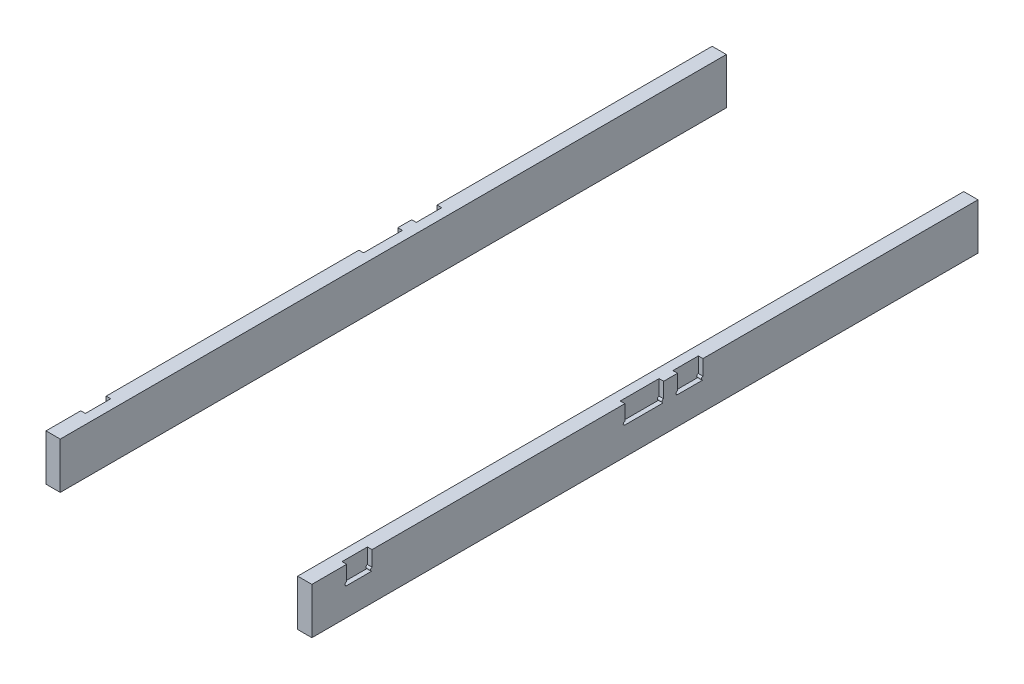
SolidWorks part; units mm, degrees
ref_plane "Front Plane" through (0, 0, 0) normal (0, 0, 1) x (1, 0, 0)
ref_plane "Top Plane" through (0, 0, 0) normal (0, 1, 0) x (1, 0, 0)
ref_plane "Right Plane" through (0, 0, 0) normal (1, 0, 0) x (0, 0, -1)
ref_plane "Plane2" through (-287.55, 0, 0) normal (-1, 0, 0) x (0, 0, 1)
sketch "Sketch8" plane through (-287.55, 0, 0) normal (-1, 0, 0) x (0, 0, 1)
  line L0 (1471.6, -400) -> (30.8, -400)
  line L1 (30.8, -400) -> (30.8, -500)
  line L2 (30.8, -500) -> (1471.6, -500)
  line L3 (1471.6, -500) -> (1471.6, -400)
  dimension "D1" = 100
  dimension "D2" = 1440.8
extrude "Boss-Extrude2" add sketch "Sketch8" against normal blind 30.8 separate body
sketch "Sketch9" plane through (-287.55, 0, 0) normal (-1, 0, 0) x (0, 0, 1)
  line L0 (680.67, -433) -> (680.67, -400)
  line L1 (680.67, -400) -> (625.67, -400)
  line L2 (625.67, -400) -> (625.67, -433)
  line L3 (625.67, -440) -> (680.67, -440)
  line L4 (30.8, -400) -> (30.8, -500) construction
  arc A0 (625.67, -433) -> (625.67, -440) centre (625.67, -436.5) ccw
  arc A1 (680.67, -440) -> (680.67, -433) centre (680.67, -436.5) ccw
  dimension "D6" = 3.5
  dimension "D7" = 3.5
  dimension "D1" = 594.87
  dimension "D2" = 55
  dimension "D3" = 36.5
  dimension "D4" = 36.5
  dimension "D5" = 40
extrude "Cut-Extrude4" cut sketch "Sketch9" against normal blind 10
sketch "Sketch10" plane through (-287.55, 0, 0) normal (-1, 0, 0) x (0, 0, 1)
  line L0 (794.66, -433.0349) -> (794.66, -400)
  line L1 (794.66, -400) -> (710.67, -400)
  line L2 (710.67, -400) -> (710.67, -433.0834)
  line L3 (709.9103, -440) -> (795.1527, -440)
  line L4 (680.67, -433) -> (680.67, -400) construction
  arc A0 (710.67, -433.0834) -> (709.9103, -440) centre (709.9103, -436.5) cw
  arc A1 (795.1527, -440) -> (794.66, -433.0349) centre (795.1527, -436.5) ccw
  dimension "D5" = 3.5
  dimension "D6" = 3.5
  dimension "D1" = 30
  dimension "D2" = 40
  dimension "D3" = 36.5
  dimension "D4" = 36.5
  dimension "D7" = 83.99
extrude "Cut-Extrude5" cut sketch "Sketch10" against normal blind 10
sketch "Sketch11" plane through (-287.55, 0, 0) normal (-1, 0, 0) x (0, 0, 1)
  line L0 (1396.47, -433.0349) -> (1396.47, -400)
  line L1 (1396.47, -400) -> (1341.47, -400)
  line L2 (1341.47, -400) -> (1341.47, -433.0834)
  line L3 (1340.7103, -440) -> (1396.9627, -440)
  line L4 (794.66, -433.0349) -> (794.66, -400) construction
  arc A0 (1341.47, -433.0834) -> (1340.7103, -440) centre (1340.7103, -436.5) cw
  arc A1 (1396.9627, -440) -> (1396.47, -433.0349) centre (1396.9627, -436.5) ccw
  dimension "D5" = 3.5
  dimension "D7" = 3.5
  dimension "D1" = 546.81
  dimension "D2" = 40
  dimension "D3" = 55
  dimension "D4" = 36.5
  dimension "D6" = 36.5
extrude "Cut-Extrude6" cut sketch "Sketch11" against normal blind 10
ref_plane "Plane3" through (287.55, 0, 0) normal (1, 0, 0) x (0, 0, -1)
sketch "Sketch16" plane through (287.55, 0, 0) normal (1, 0, 0) x (0, 0, -1)
  line L0 (-30.8, -400) -> (-1471.6, -400)
  line L1 (-1471.6, -400) -> (-1471.6, -500)
  line L2 (-1471.6, -500) -> (-30.8, -500)
  line L3 (-30.8, -500) -> (-30.8, -400)
  line L4 (-30.8, -400) -> (-30.8, -500) construction
  dimension "D1" = 100
  dimension "D2" = 1440.8
extrude "Boss-Extrude3" add sketch "Sketch16" against normal blind 30.8 separate body
sketch "Sketch17" plane through (287.55, 0, 0) normal (1, 0, 0) x (0, 0, -1)
  line L0 (-1396.4, -400) -> (-1396.4, -433)
  line L1 (-1396.4, -440) -> (-1341.4, -440)
  line L2 (-1341.4, -433) -> (-1341.4, -400)
  line L3 (-1341.4, -400) -> (-1396.4, -400)
  line L4 (-30.8, -500) -> (-30.8, -400) construction
  arc A0 (-1396.4, -433) -> (-1396.4, -440) centre (-1396.4, -436.5) ccw
  arc A1 (-1341.4, -440) -> (-1341.4, -433) centre (-1341.4, -436.5) cw
  dimension "D1" = 1310.6
extrude "Cut-Extrude7" cut sketch "Sketch17" against normal blind 10
sketch "Sketch18" plane through (287.55, 0, 0) normal (1, 0, 0) x (0, 0, -1)
  line L0 (-794.65, -400) -> (-794.65, -433)
  line L1 (-794.65, -440) -> (-710.66, -440)
  line L2 (-710.66, -433) -> (-710.66, -400)
  line L3 (-710.66, -400) -> (-794.65, -400)
  line L4 (-30.8, -500) -> (-30.8, -400) construction
  arc A0 (-794.65, -433) -> (-794.65, -440) centre (-794.65, -436.5) ccw
  arc A1 (-710.66, -440) -> (-710.66, -433) centre (-710.66, -436.5) cw
  dimension "D1" = 679.86
extrude "Cut-Extrude8" cut sketch "Sketch18" against normal blind 10
sketch "Sketch19" plane through (287.55, 0, 0) normal (1, 0, 0) x (0, 0, -1)
  line L0 (-680.67, -400) -> (-680.67, -433)
  line L1 (-680.67, -440) -> (-625.67, -440)
  line L2 (-625.67, -433) -> (-625.67, -400)
  line L3 (-625.67, -400) -> (-680.67, -400)
  line L4 (-30.8, -500) -> (-30.8, -400) construction
  arc A0 (-680.67, -433) -> (-680.67, -440) centre (-680.67, -436.5) ccw
  arc A1 (-625.67, -440) -> (-625.67, -433) centre (-625.67, -436.5) cw
  dimension "D1" = 594.87
extrude "Cut-Extrude9" cut sketch "Sketch19" against normal blind 10
